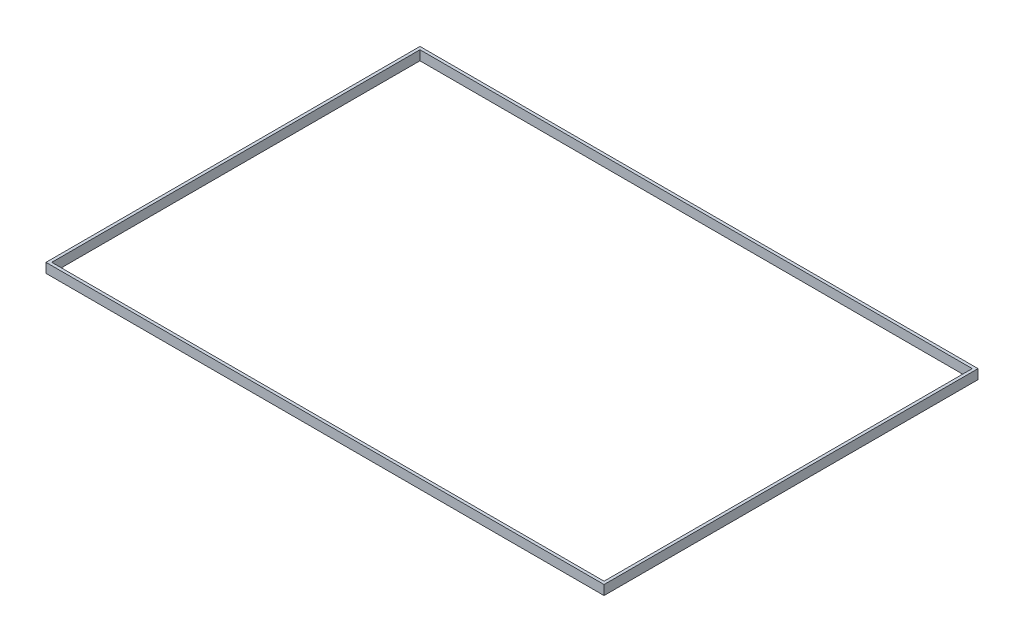
SolidWorks part; units mm, degrees
ref_plane "Front Plane" through (0, 0, 0) normal (0, 0, 1) x (1, 0, 0)
ref_plane "Top Plane" through (0, 0, 0) normal (0, 1, 0) x (1, 0, 0)
ref_plane "Right Plane" through (0, 0, 0) normal (1, 0, 0) x (0, 0, -1)
sketch "Sketch1" plane through (0, 0, 0) normal (0, 1, 0) x (1, 0, 0)
  line L0 (19.05, 19.05) -> (19.05, 2457.45)
  line L1 (0, 0) -> (3695.7, 0)
  line L2 (0, 0) -> (0, 2476.5)
  line L3 (0, 2476.5) -> (3695.7, 2476.5)
  line L4 (3695.7, 0) -> (3695.7, 2476.5)
  line L5 (19.05, 2457.45) -> (3676.65, 2457.45)
  line L6 (3676.65, 19.05) -> (3676.65, 2457.45)
  line L7 (19.05, 19.05) -> (3676.65, 19.05)
  dimension "D1" = 3695.7
  dimension "D2" = 2476.5
  dimension "D3" = 19.05
extrude "Boss-Extrude1" add sketch "Sketch1" along normal blind 63.5
